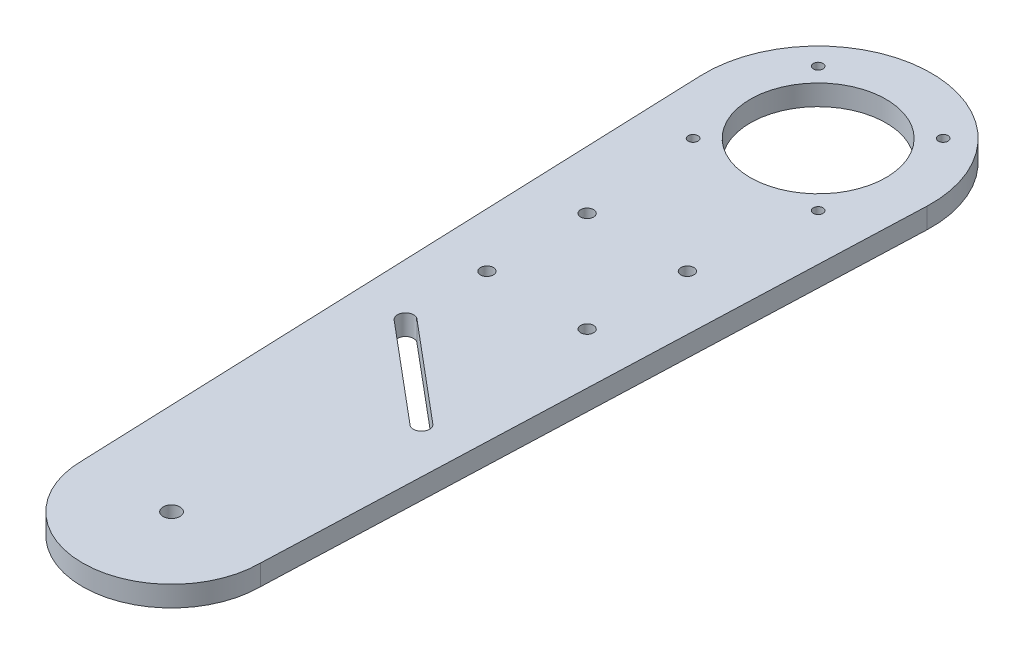
SolidWorks part; units mm, degrees
ref_plane "Front Plane" through (0, 0, 0) normal (0, 0, 1) x (1, 0, 0)
ref_plane "Top Plane" through (0, 0, 0) normal (0, 1, 0) x (1, 0, 0)
ref_plane "Right Plane" through (0, 0, 0) normal (1, 0, 0) x (0, 0, -1)
sketch "Sketch1" plane through (0, 0, 0) normal (0, 1, 0) x (1, 0, 0)
  line L0 (27.5, 0) -> (34.9753, 198.6841)
  line L1 (-27.5, 0) -> (-34.9753, 198.6841)
  arc A0 (-27.5, 0) -> (27.5, 0) centre (0, 0) ccw
  arc A3 (34.9753, 198.6841) -> (-34.9753, 198.6841) centre (0, 200) ccw
  dimension "D1" = 55
  dimension "D3" = 200
  dimension "D2" = 70
extrude "Boss-Extrude1" add sketch "Sketch1" along normal blind 6.35
sketch "Sketch2" plane through (0, 6.35, 0) normal (0, 1, 0) x (1, 0, 0)
  circle A0 centre (0, 0) radius 2.6
  dimension "D1" = 5.2
extrude "Cut-Extrude1" cut sketch "Sketch2" against normal through all
sketch "Esquisse4" plane through (0, 6.35, 0) normal (0, 1, 0) x (1, 0, 0)
  circle A0 centre (0, 200) radius 35
  arc A1 (34.9753, 198.6841) -> (-34.9753, 198.6841) centre (0, 200) ccw construction
sketch "Esquisse3" plane through (0, 6.35, 0) normal (0, 1, 0) x (1, 0, 0)
  circle A1 centre (0, 200) radius 21
  dimension "D1" = 42
extrude "Enlèv. mat.-Extru.2" cut sketch "Esquisse3" against normal through all
sketch "Esquisse5" plane through (0, 6.35, 0) normal (0, 1, 0) x (1, 0, 0)
  circle A0 centre (0, 200) radius 27.35
  dimension "D1" = 54.7
sketch "Esquisse7" plane through (0, 6.35, 0) normal (0, 1, 0) x (1, 0, 0)
  line L0 (-19.3394, 180.6606) -> (19.3394, 180.6606) construction
  line L1 (19.3394, 180.6606) -> (19.3394, 219.3394) construction
  line L2 (19.3394, 219.3394) -> (-19.3394, 219.3394) construction
  line L3 (-19.3394, 219.3394) -> (-19.3394, 180.6606) construction
  circle A0 centre (-19.3394, 219.3394) radius 1.5
  circle A1 centre (0, 200) radius 27.35 construction
  circle A2 centre (19.3394, 219.3394) radius 1.5
  circle A3 centre (19.3394, 180.6606) radius 1.5
  circle A4 centre (-19.3394, 180.6606) radius 1.5
  point P12 (0, 180.6606)
  dimension "D1" = 3
extrude "Enlèv. mat.-Extru.3" cut sketch "Esquisse7" against normal through all
sketch "Esquisse10" plane through (0, 0, 0) normal (1, 0, 0) x (0, 0, -1)
  line L0 (200, 30.779) -> (200, -18.079) construction
  point P4 (200, 6.35)
sketch "Esquisse8" plane through (0, 6.35, 0) normal (0, 1, 0) x (1, 0, 0)
  line L0 (18.4733, 182.1606) -> (20.2054, 182.1606)
  line L1 (20.2054, 182.1606) -> (21.0714, 180.6606)
  line L2 (21.0714, 180.6606) -> (20.2054, 179.1606)
  line L3 (20.2054, 179.1606) -> (18.4733, 179.1606)
  line L4 (18.4733, 179.1606) -> (17.6073, 180.6606)
  line L5 (17.6073, 180.6606) -> (18.4733, 182.1606)
  circle A1 centre (19.3394, 180.6606) radius 1.5 construction
extrude "Enlèv. mat.-Extru.5" [suppressed] cut sketch "Esquisse8" against normal through all
pattern_circular "Répétition circulaire1" [suppressed] count 4 over 360 about axis through (0, 30.779, -200) along (0, -1, 0)
sketch "Sketch4" plane through (0, 6.35, 0) normal (0, 1, 0) x (1, 0, 0)
  line L0 (15.3209, 61.9885) -> (-15.3209, 87.7) construction
  line L1 (13.7139, 60.0734) -> (-16.9279, 85.7849)
  line L2 (16.9279, 63.9036) -> (-13.7139, 89.6151)
  arc A0 (13.7139, 60.0734) -> (16.9279, 63.9036) centre (15.3209, 61.9885) ccw
  arc A1 (-13.7139, 89.6151) -> (-16.9279, 85.7849) centre (-15.3209, 87.7) ccw
  point P4 (0, 74.8442)
  dimension "D1" = 2.5
extrude "Cut-Extrude3" cut sketch "Sketch4" against normal through all
sketch "Sketch5" plane through (0, 0, 0) normal (0, -1, 0) x (1, 0, 0)
  circle A1 centre (-15.65, -113.2) radius 2
  circle A2 centre (15.35, -113.2) radius 2
  circle A3 centre (15.35, -144.2) radius 2
  circle A4 centre (15.35, -113.2) radius 2
  dimension "D1" = 4
extrude "Cut-Extrude4" cut sketch "Sketch5" against normal through all
sketch "Sketch6" plane through (0, 6.35, 0) normal (0, 1, 0) x (1, 0, 0)
  circle A0 centre (-15.65, 144.2) radius 2
  circle A1 centre (-15.65, 113.2) radius 2
  circle A2 centre (15.35, 113.2) radius 2
  circle A3 centre (15.35, 144.2) radius 2
  dimension "D1" = 4
extrude "Cut-Extrude5" cut sketch "Sketch6" against normal through all
